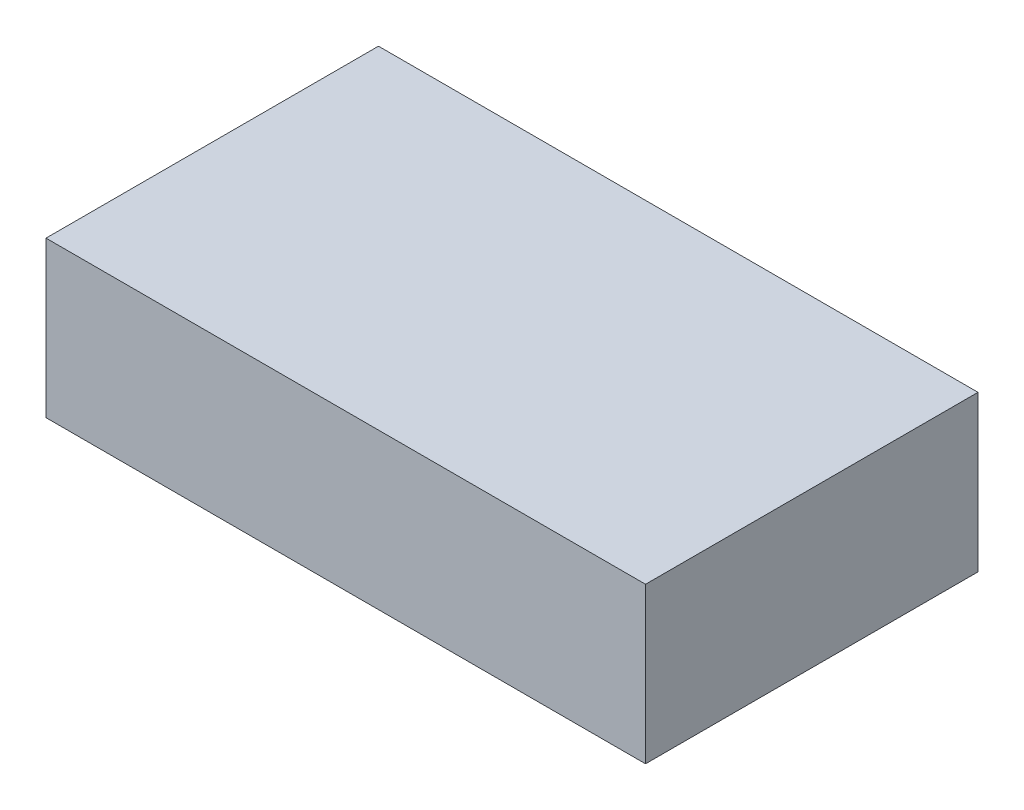
SolidWorks part; units mm, degrees
ref_plane "Front Plane" through (0, 0, 0) normal (0, 0, 1) x (1, 0, 0)
ref_plane "Top Plane" through (0, 0, 0) normal (0, 1, 0) x (1, 0, 0)
ref_plane "Right Plane" through (0, 0, 0) normal (1, 0, 0) x (0, 0, -1)
sketch "Sketch1" plane through (0, 0, 0) normal (0, 0, 1) x (1, 0, 0)
  line L1 (-68.7035, -17.821) -> (68.7035, -17.821)
  line L2 (-68.7035, -17.821) -> (-68.7035, 17.821)
  line L3 (-68.7035, 17.821) -> (68.7035, 17.821)
  line L4 (68.7035, -17.821) -> (68.7035, 17.821)
  line L5 (-68.7035, -17.821) -> (68.7035, 17.821) construction
  line L6 (-68.7035, 17.821) -> (68.7035, -17.821) construction
  point P0 (0, 0)
extrude "Boss-Extrude1" add sketch "Sketch1" along normal blind 76.2 contours L1 L4 L3 L2
